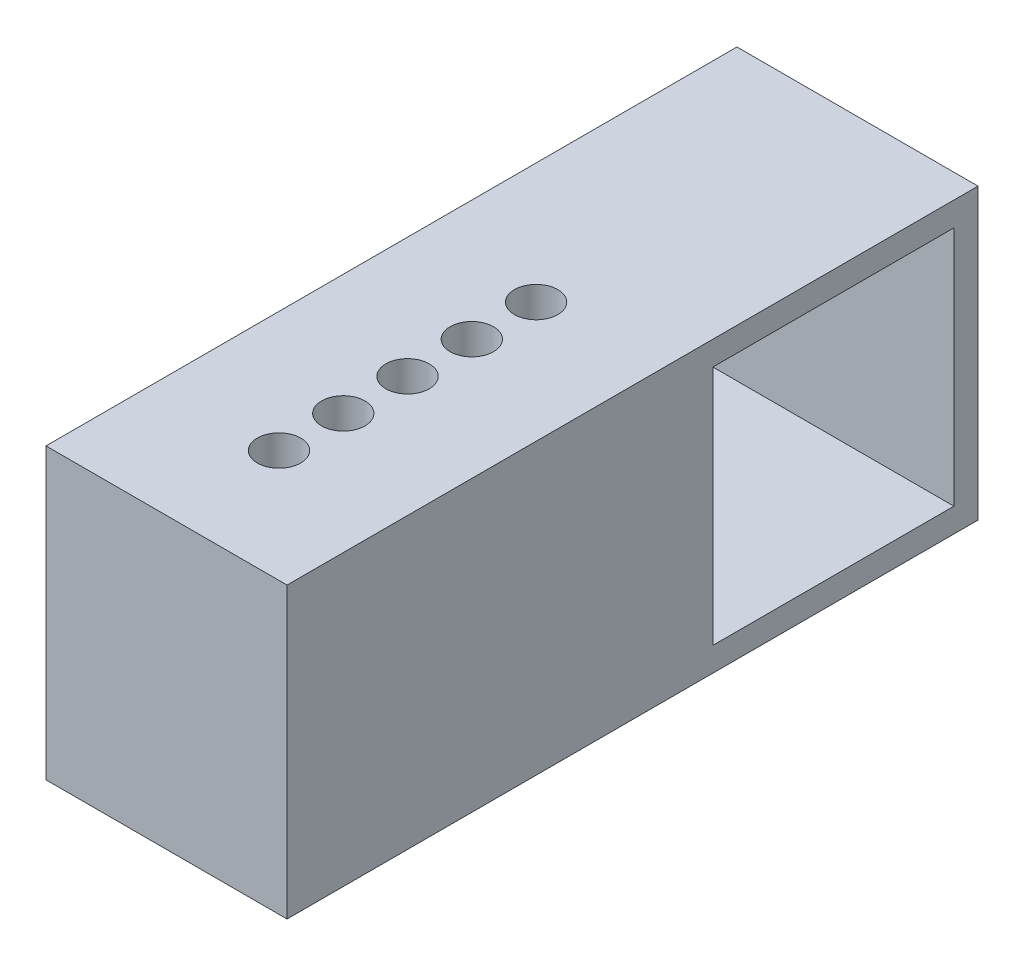
SolidWorks part; units mm, degrees
ref_plane "Piano frontale" through (0, 0, 0) normal (0, 0, 1) x (1, 0, 0)
ref_plane "Piano superiore" through (0, 0, 0) normal (0, 1, 0) x (1, 0, 0)
ref_plane "Piano destro" through (0, 0, 0) normal (1, 0, 0) x (0, 0, -1)
sketch "Schizzo1" plane through (0, 0, 0) normal (1, 0, 0) x (0, 0, -1)
  line L0 (-9, 9) -> (-34, 9)
  line L1 (-9, -9) -> (9, -9)
  line L2 (-9, -9) -> (-9, 9)
  line L3 (-9, 9) -> (9, 9)
  line L4 (9, -9) -> (9, 9)
  line L5 (-9, -9) -> (9, 9) construction
  line L6 (-9, 9) -> (9, -9) construction
  line L7 (-7.5, -7.5) -> (7.5, -7.5)
  line L8 (-7.5, -7.5) -> (-7.5, 7.5)
  line L9 (-7.5, 7.5) -> (7.5, 7.5)
  line L10 (7.5, -7.5) -> (7.5, 7.5)
  line L11 (-7.5, -7.5) -> (7.5, 7.5) construction
  line L12 (-7.5, 7.5) -> (7.5, -7.5) construction
  line L13 (-34, 9) -> (-34, -9)
  line L14 (-34, -9) -> (-9, -9)
  point P0 (0, 0)
  point P6 (0, 0)
  dimension "D1" = 18
  dimension "D2" = 15
  dimension "D3" = 18
  dimension "D4" = 15
  dimension "D5" = 25
extrude "Estrusione-Estrusione1" add sketch "Schizzo1" along normal blind 15 contours L13 L14 L2 L0 | L1 L4 L3 L2 L10 L7 L8 L9
sketch "Schizzo2" plane through (0, 9, 0) normal (0, 1, 0) x (1, 0, 0)
  line L2 (15, -34) -> (0, -34) construction
  line L3 (0, 9) -> (0, -34) construction
  circle A0 centre (7.5, -31) radius 1.35
  circle A1 centre (7.5, -27) radius 1.35
  circle A2 centre (7.5, -23) radius 1.35
  circle A3 centre (7.5, -19) radius 1.35
  circle A4 centre (7.5, -15) radius 1.35
  circle A5 centre (7.5, -11) radius 1.35
  dimension "D1" = 3
  dimension "D2" = 7.5
  dimension "D3" = 2.7
  dimension "D4" = 6
extrude "Taglio-Estrusione1" cut sketch "Schizzo2" along direction (0, 1, 0) on the side against the normal through all and the other way through all contours A4 | A3 | A2 | A1 | A0
sketch "Schizzo3" plane through (0, 9, 0) normal (0, 1, 0) x (1, 0, 0)
  line L0 (15, -34) -> (0, -34) construction
  line L1 (15, 9) -> (15, -34) construction
  circle A0 centre (7.5, -11) radius 1.35
  dimension "D2" = 2.7
  dimension "D1" = 23
  dimension "D3" = 7.5
extrude "Taglio-Estrusione2" cut sketch "Schizzo3" against normal blind 15
sketch "Schizzo4" plane through (0, -9, 0) normal (0, -1, 0) x (1, 0, 0)
  line L0 (15, 34) -> (15, -9) construction
  line L1 (15, 34) -> (0, 34) construction
  circle A0 centre (7.5, 31) radius 1.35
  dimension "D1" = 2.7
  dimension "D3" = 3
  dimension "D2" = 7.5
extrude "Taglio-Estrusione3" cut sketch "Schizzo4" against normal blind 15
